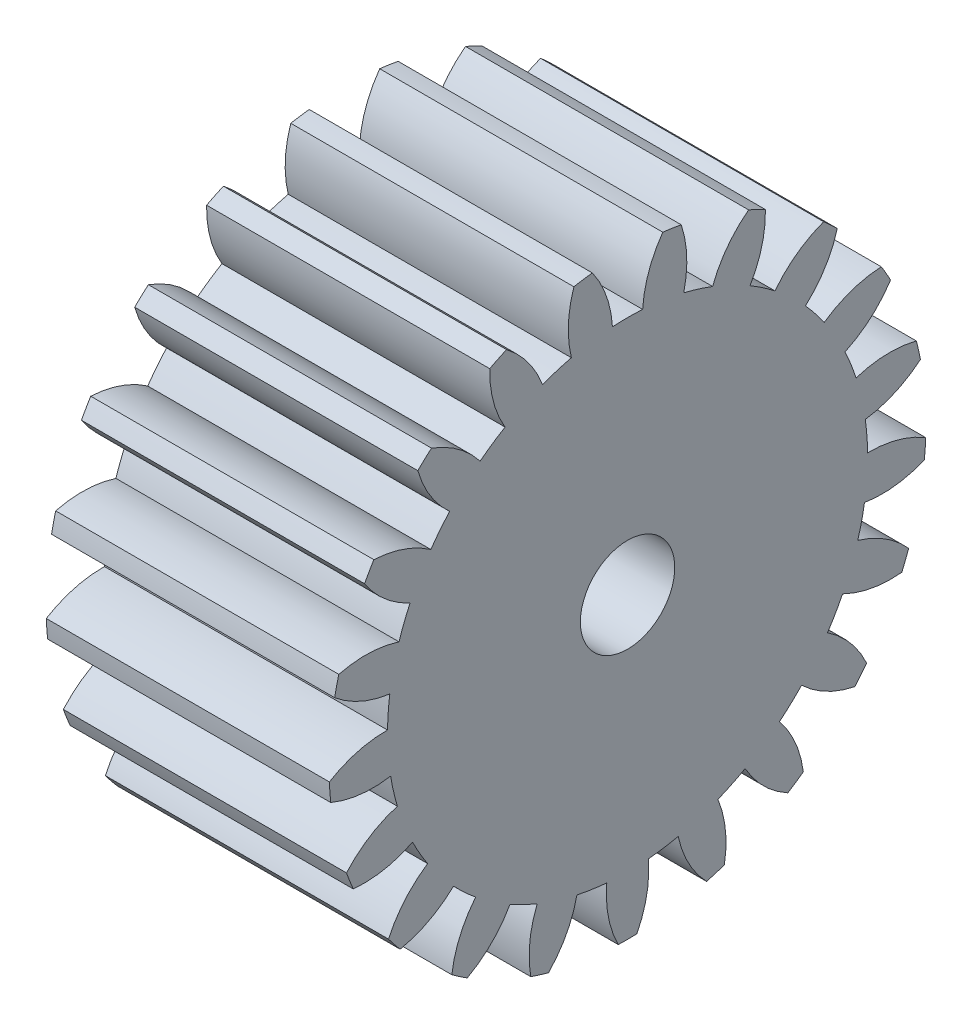
SolidWorks part; units mm, degrees
ref_plane "Plane1" through (0, 0, 0) normal (0, 0, 1) x (1, 0, 0)
ref_plane "Plane2" through (0, 0, 0) normal (0, 1, 0) x (1, 0, 0)
ref_plane "Plane3" through (0, 0, 0) normal (1, 0, 0) x (0, 0, -1)
sketch "HoldingSke" plane through (0, 0, 0) normal (0, 1, 0) x (1, 0, 0)
  line L0 (0, 0) -> (0.679, -0.2606)
  line L1 (-15, 0) -> (100, 0) construction
  line L2 (0, 0) -> (-2.1039, 2.3779)
  line L3 (0, 0) -> (-11.863, 4.5341)
  line L4 (0, 0) -> (8.0624, 3.0949)
  line L5 (0, 0) -> (-46.8476, -17.4728)
  line L6 (0, 0) -> (-12.4344, -8.3896)
  line L7 (-2.1039, 2.3779) -> (8.6586, 51.2059)
  line L8 (-76.2, 54.61) -> (-75.3, 54.61)
  line L9 (-67.7845, 28.3722) -> (-49.3413, 33.142)
  line L10 (-76.2, 71.12) -> (104.1128, 71.12)
  line L11 (0, 0) -> (-15, 0)
  line L12 (-76.2, 101.6) -> (-76.151, 101.6)
  line L13 (24.9733, 27.94) -> (52.9518, 28.4284)
  line L14 (24.9733, 27.94) -> (24.9743, 27.94)
  line L15 (24.9733, 27.94) -> (100.4006, 29.5858)
  line L16 (-63.627, -1.375) -> (-12.827, -1.375)
  circle A0 centre (0, 0) radius 2.5
  circle A1 centre (0, 0) radius 12.7178
  circle A2 centre (0, 0) radius 37.5
  circle A3 centre (0, 0) radius 2.5
  dimension "MHD" = 25.4355
  dimension "Hub_dia" = 75
  dimension "Bore" = 5
  dimension "MBD" = 5
  dimension "Num_teeth" = 21
  dimension "Pitch" = 0.7273
  dimension "Overall_len" = 50
  dimension "Show_teeth" = 21
  dimension "Thickness" = 15
  dimension "OAL" = 50.0001
  dimension "T_dim" = 0.9
  dimension "Ap" = 14.5
  dimension "H" = 19.05
  dimension "Pitch_radius" = 180.3128
  dimension "Width" = 15
  dimension "Backlash" = 0.049
  dimension "Addendum_fac" = 1
  dimension "Dedendum_fac" = 1.25
  dimension "Clearance_fac" = 0.25
  dimension "Dedendum_add" = 0.001
  dimension "Module" = 1.375
sketch "BasProSke" plane through (0, 0, 0) normal (0, 1, 0) x (1, 0, 0)
  line L0 (-10, 0) -> (60, 0) construction
  line L1 (0, 0) -> (0, 15.8125)
  line L2 (0, 0) -> (15, 0)
  line L3 (15, 0) -> (15, 15.8125)
  line L4 (15, 15.8125) -> (0, 15.8125)
  dimension "Thickness" = 15
  dimension "Diameter" = 31.625
revolve "Base-Revolve" add sketch "BasProSke" angle 360 about L0
sketch "TooCutSke" plane through (0, 0, 0) normal (1, 0, 0) x (0, 0, -1)
  line L1 (0, 0) -> (0, 107) construction
  line L2 (0, 0) -> (-1.1646, 14.3904) construction
  line L3 (0, 0) -> (-4.2934, 28.4849) construction
  line L4 (-1.1646, 14.3904) -> (-2.1467, 14.2424) construction
  arc A0 (0.7994, 12.6926) -> (-0.7994, 12.6926) centre (0, 0) ccw
  arc A1 (1.8845, 15.7254) -> (-1.8845, 15.7254) centre (0, 0) ccw
  circle A2 centre (0, 0) radius 14.4375 construction
  circle A3 centre (0, 0) radius 13.9776 construction
  arc A4 (-0.7994, 12.6926) -> (-1.8845, 15.7254) centre (-6.5636, 12.3407) ccw
  arc A5 (1.8845, 15.7254) -> (0.7994, 12.6926) centre (6.5636, 12.3407) ccw
  dimension "Root_dia" = 25.4355
  dimension "Overcut_dia" = 31.6758
  dimension "Pitch_dia" = 28.875
  dimension "Base_dia" = 27.9553
  dimension "Flank_rad" = 5.775
  dimension "Half_ang" = 8.571
  dimension "Half_CT" = 0.9932
extrude "ToothCut" cut sketch "TooCutSke" along normal through all
fillet "Breaks" [suppressed] radius 0.0275
fillet "RootFillets" [suppressed] radius 0.3448
pattern_circular "TeethCuts" count 21 over 360 about axis through (0, 0, 0) along (1, 0, 0) of "ToothCut", "RootFillets", "Breaks"
sketch "HubNeaOneSke" plane through (0, 0, 0) normal (-1, 0, 0) x (0, 0, 1)
  circle A0 centre (0, 0) radius 12.7178
  dimension "Diameter" = 25.4355
extrude "HubNearOne" [suppressed] add sketch "HubNeaOneSke" along normal blind 35.0001
sketch "HubNeaBotSke" plane through (0, 0, 0) normal (-1, 0, 0) x (0, 0, 1)
  circle A0 centre (0, 0) radius 12.7178
  dimension "Diameter" = 25.4355
extrude "HubNearBoth" [suppressed] add sketch "HubNeaBotSke" along normal blind 17.5
ref_plane "FarPln" through (15, 0, 0) normal (1, 0, 0) x (0, 0, -1)
sketch "HubFarSke" plane through (15, 0, 0) normal (1, 0, 0) x (0, 0, -1)
  circle A0 centre (0, 0) radius 12.7178
  dimension "Diameter" = 25.4355
extrude "HubFar" [suppressed] add sketch "HubFarSke" along normal blind 17.5
sketch "BorSke" plane through (0, 0, 0) normal (1, 0, 0) x (0, 0, -1)
  circle A0 centre (0, 0) radius 2.5
  dimension "Diameter" = 5
extrude "Bore" cut sketch "BorSke" along normal mid plane 100.0001
sketch "KeySke" plane through (0, 0, 0) normal (1, 0, 0) x (0, 0, -1)
  line L0 (-1, 0) -> (-1, 3.4)
  line L1 (-1, 3.4) -> (1, 3.4)
  line L2 (1, 3.4) -> (1, 0)
  line L3 (0, 0) -> (0, 34) construction
  line L4 (-1, 0) -> (1, 0)
  dimension "Offset" = 3.4
  dimension "Width" = 2
extrude "Keyway" [suppressed] cut sketch "KeySke" along normal mid plane 100.0001
pattern_circular "Keyway2" [suppressed] count 2 every 90 about axis through (-10, 0, 0) along (1, 0, 0)
equation "' \"Module@HoldingSke\" = 6.35"
equation "' \"Num_teeth@HoldingSke\" = 12"
equation "' \"Ap@HoldingSke\" =  20"
equation "' \"Ap@HoldingSke\" = 20"
equation "' \"Width@HoldingSke\" = 0.5 * 25.4"
equation "' \"Hub_dia@HoldingSke\"= 1 * 25.4"
equation "' \"Hub_dia@HoldingSke\" = 1 * 25.4"
equation "' \"Overall_len@HoldingSke\" = 1.0 * 25.4"
equation "' \"Bore@HoldingSke\" = 0.75 * 25.4"
equation "' \"T_dim@HoldingSke\" = 0.1 * 25.4"
equation "' \"Width@KeySke\" = 0.25 * 25.4"
equation "' \"Show_teeth@HoldingSke\" = 13"
equation "' \"Backlash@HoldingSke\" = 0.009 * 25.4"
equation "' \"Addendum_fac@HoldingSke\" = 1.0"
equation "' \"Dedendum_fac@HoldingSke\" = 1.25"
equation "' \"Dedendum_add@HoldingSke\" = 0.00005 * 25.4"
equation "' \"Clearance_fac@HoldingSke\" = 0.25"
equation "\"Pitch@HoldingSke\" = 1 / \"Module@HoldingSke\""
equation "\"Overcut_dia@TooCutSke\" = (\"Num_teeth@HoldingSke\" + 2 * \"Addendum_fac@HoldingSke\") / \"Pitch@HoldingSke\" + 0.002 * 25.4"
equation "\"Pitch_dia@TooCutSke\" = \"Num_teeth@HoldingSke\" / \"Pitch@HoldingSke\""
equation "\"Base_dia@TooCutSke\" = \"Num_teeth@HoldingSke\" / \"Pitch@HoldingSke\" * cos((\"Ap@HoldingSke\"  * 3.14159265 / 180))"
equation "\"Root_dia@TooCutSke\" = (\"Num_teeth@HoldingSke\" + 2) / \"Pitch@HoldingSke\" - 2 * (\"Addendum_fac@HoldingSke\" + \"Dedendum_fac@HoldingSke\") / \"Pitch@HoldingSke\" - \"Dedendum_add@HoldingSke\" * 2"
equation "\"Half_ang@TooCutSke\" = 180 / \"Num_teeth@HoldingSke\""
equation "\"Half_CT@TooCutSke\" = \"Num_teeth@HoldingSke\" / \"Pitch@HoldingSke\" * sin((3.14159265 / 2 / \"Num_teeth@HoldingSke\")) / 2 - 7 * \"Backlash@HoldingSke\" / 4"
equation "\"Flank_rad@TooCutSke\" = \"Num_teeth@HoldingSke\" / \"Pitch@HoldingSke\" / 5"
equation "\"Radius@RootFillets\" = \"Clearance_fac@HoldingSke\" / \"Pitch@HoldingSke\" + \"Dedendum_add@HoldingSke\""
equation "\"Break_rad@Breaks\" = 0.02 / \"Pitch@HoldingSke\""
equation "\"Thickness@HoldingSke\" = \"Width@HoldingSke\""
equation "\"OAL@HoldingSke\" = \"Thickness@HoldingSke\""
equation "\"MHD@HoldingSke\" = (\"Num_teeth@HoldingSke\" + 2) / \"Pitch@HoldingSke\" - 2 * (\"Addendum_fac@HoldingSke\" + \"Dedendum_fac@HoldingSke\")  / \"Pitch@HoldingSke\" - \"Dedendum_add@HoldingSke\" * 2"
equation "\"MBD@HoldingSke\" = (\"Num_teeth@HoldingSke\" + 2) / \"Pitch@HoldingSke\" - 2 * (\"Addendum_fac@HoldingSke\" + \"Dedendum_fac@HoldingSke\")  / \"Pitch@HoldingSke\" - \"Dedendum_add@HoldingSke\" * 2 - 0.002 * 25.4"
equation "\"MHD@HoldingSke\" = ((sgn( \"MHD@HoldingSke\" - \"Hub_dia@HoldingSke\" )-1)*( \"MHD@HoldingSke\" - \"Hub_dia@HoldingSke\" ))/-2+ \"Hub_dia@HoldingSke\""
equation "\"MBD@HoldingSke\" = ((sgn( \"MBD@HoldingSke\" - \"Bore@HoldingSke\" )-1)*( \"MBD@HoldingSke\" - \"Bore@HoldingSke\" ))/-2+ \"Bore@HoldingSke\""
equation "\"OAL@HoldingSke\" = ((sgn( \"OAL@HoldingSke\" - \"Overall_len@HoldingSke\" )+1)*( \"OAL@HoldingSke\" - \"Overall_len@HoldingSke\" ))/2 + \"Overall_len@HoldingSke\" + 0.000002 * 25.4"
equation "\"Num_teeth@TeethCuts\" = int( \"Show_teeth@HoldingSke\" ) + 1"
equation "\"Num_teeth@TeethCuts\" = ((sgn( \"Num_teeth@TeethCuts\" - \"Num_teeth@HoldingSke\" )-1)*( \"Num_teeth@TeethCuts\" - \"Num_teeth@HoldingSke\" ))/-2+ \"Num_teeth@HoldingSke\""
equation "\"Num_teeth@TeethCuts\" = ((sgn( \"Num_teeth@TeethCuts\" - 2.0)+1)*( \"Num_teeth@TeethCuts\" - 2.0))/2 +2.0"
equation "\"Angle@TeethCuts\" = 360.0 / \"Num_teeth@HoldingSke\""
equation "\"Diameter@BasProSke\" = (\"Num_teeth@HoldingSke\" + 2 * \"Addendum_fac@HoldingSke\") / \"Pitch@HoldingSke\""
equation "\"Thickness@BasProSke\"  = \"Thickness@HoldingSke\""
equation "' \"Fillet_rad@BasProSke\" =  \"Thickness@HoldingSke\" * 0.05"
equation "' \"Fillet_rad@BasProSke\" = \"Thickness@HoldingSke\" * 0.05"
equation "\"MHD@HoldingSke\" = ((sgn( \"MHD@HoldingSke\" - \"Root_dia@TooCutSke\" )-1)*( \"MHD@HoldingSke\" - \"Root_dia@TooCutSke\" ))/-2+ \"Root_dia@TooCutSke\""
equation "\"Diameter@HubNeaOneSke\" = \"MHD@HoldingSke\""
equation "\"Length@HubNearOne\" = \"OAL@HoldingSke\" - \"Thickness@BasProSke\""
equation "\"Diameter@HubNeaBotSke\" = \"MHD@HoldingSke\""
equation "\"Length@HubNearBoth\" = ( \"OAL@HoldingSke\" - \"Thickness@BasProSke\" ) / 2.0"
equation "\"Thickness@FarPln\" = \"Thickness@BasProSke\""
equation "\"Diameter@HubFarSke\" = \"MHD@HoldingSke\""
equation "\"Length@HubFar\" = ( \"OAL@HoldingSke\" - \"Thickness@BasProSke\" ) / 2.0"
equation "\"Diameter@BorSke\" = \"MBD@HoldingSke\""
equation "\"D1@Bore\" = \"OAL@HoldingSke\" * 2.0"
equation "\"D1@Keyway\" = \"OAL@HoldingSke\" * 2.0"
equation "\"Offset@KeySke\" = \"T_dim@HoldingSke\" + \"MBD@HoldingSke\" / 2.0"
